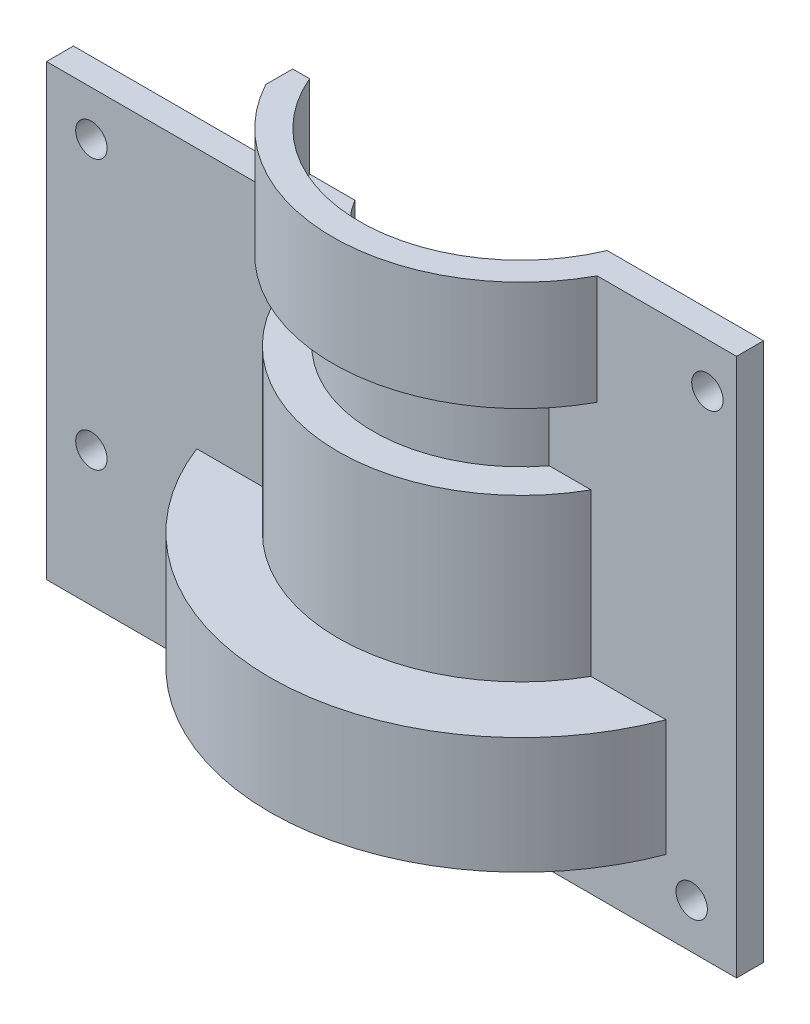
SolidWorks part; units mm, degrees
material "PET"
ref_plane "Piano frontale" through (0, 0, 0) normal (0, 0, 1) x (1, 0, 0)
ref_plane "Piano superiore" through (0, 0, 0) normal (0, 1, 0) x (1, 0, 0)
ref_plane "Piano destro" through (0, 0, 0) normal (1, 0, 0) x (0, 0, -1)
sketch "Schizzo1" plane through (0, 0, 0) normal (0, 0, 1) x (1, 0, 0)
  line L1 (38.45, -30) -> (-38.45, -30)
  line L2 (38.45, -30) -> (38.45, 30)
  line L3 (38.45, 30) -> (-38.45, 30)
  line L4 (-38.45, -30) -> (-38.45, 30)
  line L5 (38.45, -30) -> (-38.45, 30) construction
  line L6 (38.45, 30) -> (-38.45, -30) construction
  point P0 (0, 0)
  dimension "D1" = 60
  dimension "D2" = 76.9
extrude "Estrusione-Estrusione1" add sketch "Schizzo1" along normal blind 3
ref_plane "Piano1" through (0, 0, -7) normal (0, 0, -1) x (-1, 0, 0)
sketch "Schizzo2" plane through (0, 0, -7) normal (0, 0, -1) x (-1, 0, 0)
  line L0 (-4.45, 39.6639) -> (-4.45, -45.6471)
  line L4 (38.45, -30) -> (38.45, 30)
  line L5 (38.45, 30) -> (-38.45, 30)
  line L6 (-38.45, 30) -> (-38.45, -30)
  line L7 (-38.45, -30) -> (38.45, -30)
  line L8 (38.45, -30) -> (38.45, 30)
  line L9 (38.45, 30) -> (-38.45, 30)
  line L10 (-38.45, 30) -> (-38.45, -30)
  line L11 (-38.45, -30) -> (38.45, -30)
  line L19 (-1.9489, 34.6514) -> (-1.9489, -22)
  line L20 (-1.9489, -22) -> (23.55, -22)
  line L21 (23.55, -22) -> (23.55, -9)
  line L22 (23.55, -9) -> (15.95, -9)
  line L25 (15.95, -9) -> (15.95, 9)
  line L26 (15.95, 9) -> (12.05, 9)
  line L29 (12.05, 9) -> (12.05, 17.8)
  line L31 (16.55, 17.8) -> (16.55, 34.6514)
  line L32 (16.55, 34.6514) -> (-1.9489, 34.6514)
  line L33 (12.05, 17.8) -> (16.55, 17.8)
  dimension "D2" = 34
  dimension "D3" = 8
  dimension "D4" = 13
  dimension "D6" = 18
  dimension "D8" = 8.8
  dimension "D9" = 28
  dimension "D11" = 20.4
  dimension "D13" = 16.5
  dimension "D14" = 21
  dimension "D1" = 0
revolve "Rivoluzione2" add sketch "Schizzo2" angle 180 about L0
sketch "Schizzo3" plane through (38.45, 0, 0) normal (1, 0, 0) x (0, 0, -1)
  line L0 (-3, 30) -> (0, 30) construction
  line L1 (-42.2716, 49.0759) -> (40.5859, 49.0759)
  line L2 (-42.2716, 49.0759) -> (-42.2716, 30)
  line L3 (-42.2716, 30) -> (40.5859, 30)
  line L4 (40.5859, 49.0759) -> (40.5859, 30)
extrude "Taglio-Estrusione1" cut sketch "Schizzo3" against normal through all
sketch "Schizzo8" plane through (0, 0, -7) normal (0, 0, -1) x (-1, 0, 0)
  line L0 (13.55, 27) -> (13.55, 30)
  line L33 (-4.45, 30) -> (-4.45, -22)
  line L34 (-1.9489, -19) -> (20.55, -19)
  line L35 (20.55, -19) -> (20.55, -12)
  line L36 (20.55, -12) -> (12.95, -12)
  line L37 (-1.9489, 30) -> (-6.9511, 30)
  line L38 (-6.9511, 30) -> (-6.9511, -22)
  line L39 (-6.9511, -22) -> (-1.9489, -22)
  line L40 (-1.9489, -22) -> (-1.9489, 30)
  line L41 (-1.9489, 30) -> (-6.9511, 30)
  line L42 (-6.9511, 30) -> (-6.9511, -22)
  line L43 (16.55, 30) -> (-1.9489, 30)
  line L44 (-1.9489, 30) -> (-1.9489, -22)
  line L45 (-1.9489, -22) -> (23.55, -22)
  line L46 (23.55, -22) -> (23.55, -9)
  line L47 (23.55, -9) -> (15.95, -9)
  line L48 (15.95, -9) -> (15.95, 9)
  line L49 (15.95, 9) -> (12.05, 9)
  line L50 (12.05, 9) -> (12.05, 17.8)
  line L51 (12.05, 17.8) -> (16.55, 17.8)
  line L52 (16.55, 17.8) -> (16.55, 30)
  line L53 (16.55, 30) -> (-1.9489, 30)
  line L54 (-1.9489, 30) -> (-1.9489, -22)
  line L55 (-1.9489, -22) -> (23.55, -22)
  line L56 (23.55, -22) -> (23.55, -9)
  line L57 (23.55, -9) -> (15.95, -9)
  line L58 (15.95, -9) -> (15.95, 9)
  line L59 (15.95, 9) -> (12.05, 9)
  line L60 (12.05, 9) -> (12.05, 17.8)
  line L61 (12.05, 17.8) -> (16.55, 17.8)
  line L62 (16.55, 17.8) -> (16.55, 30)
  line L63 (-6.9511, -22) -> (-1.9489, -22)
  line L64 (-1.9489, -22) -> (-1.9489, 30)
  line L65 (12.95, -12) -> (12.95, 6)
  line L66 (12.95, 6) -> (9.05, 6)
  line L67 (9.05, 6) -> (9.05, 20.8)
  line L68 (9.05, 20.8) -> (13.55, 20.8)
  line L69 (13.55, 20.8) -> (13.55, 27)
  line L71 (13.55, 27) -> (-1.9489, 27) construction
  dimension "D1" = 0
  dimension "D2" = 0
  dimension "D3" = 3
revolve "Taglia-Rivoluzione1" cut sketch "Schizzo8" angle 360 about L33
sketch "Schizzo5" plane through (38.45, 0, 0) normal (1, 0, 0) x (0, 0, -1)
  line L0 (0, -30) -> (0, 30) construction
  line L1 (0, 49.2201) -> (31.4598, 49.2201)
  line L2 (0, 49.2201) -> (0, -22.5376)
  line L3 (0, -22.5376) -> (31.4598, -22.5376)
  line L4 (31.4598, 49.2201) -> (31.4598, -22.5376)
extrude "Taglio-Estrusione2" cut sketch "Schizzo5" against normal through all
sketch "Schizzo6" plane through (0, 0, 3) normal (0, 0, 1) x (1, 0, 0)
  line L6 (-38.45, 30) -> (-14.0162, 30)
  line L7 (-38.45, 30) -> (-38.45, 20)
  line L8 (-38.45, 20) -> (-14.0162, 20)
  line L9 (-14.0162, 30) -> (-14.0162, 20)
  dimension "D1" = 10
extrude "Taglio-Estrusione3" cut sketch "Schizzo6" against normal through all
sketch "Schizzo7" plane through (0, 0, 3) normal (0, 0, 1) x (1, 0, 0)
  line L0 (-38.45, 15) -> (-38.45, 20)
  line L1 (-38.45, 20) -> (-38.45, -30) construction
  line L2 (-38.45, 15) -> (-33.45, 15)
  line L3 (-38.45, -30) -> (-38.45, -15)
  line L4 (-38.45, -15) -> (-33.45, -15)
  line L5 (38.45, 30) -> (35.2, 30)
  line L6 (38.45, 30) -> (22.9162, 30) construction
  line L7 (35.2, 30) -> (35.2, 25)
  line L8 (38.45, -30) -> (33.45, -30)
  line L9 (-38.45, -30) -> (38.45, -30) construction
  line L10 (33.45, -30) -> (33.45, -25)
  circle A0 centre (-33.45, 15) radius 1.75
  circle A1 centre (-33.45, -15) radius 1.75
  circle A2 centre (33.45, -25) radius 1.75
  circle A3 centre (35.2, 25) radius 1.75
  dimension "D4" = 3.5
  dimension "D1" = 5
  dimension "D2" = 5
  dimension "D3" = 15
  dimension "D5" = 3.25
  dimension "D6" = 5
extrude "Taglio-Estrusione4" cut sketch "Schizzo7" against normal through all
